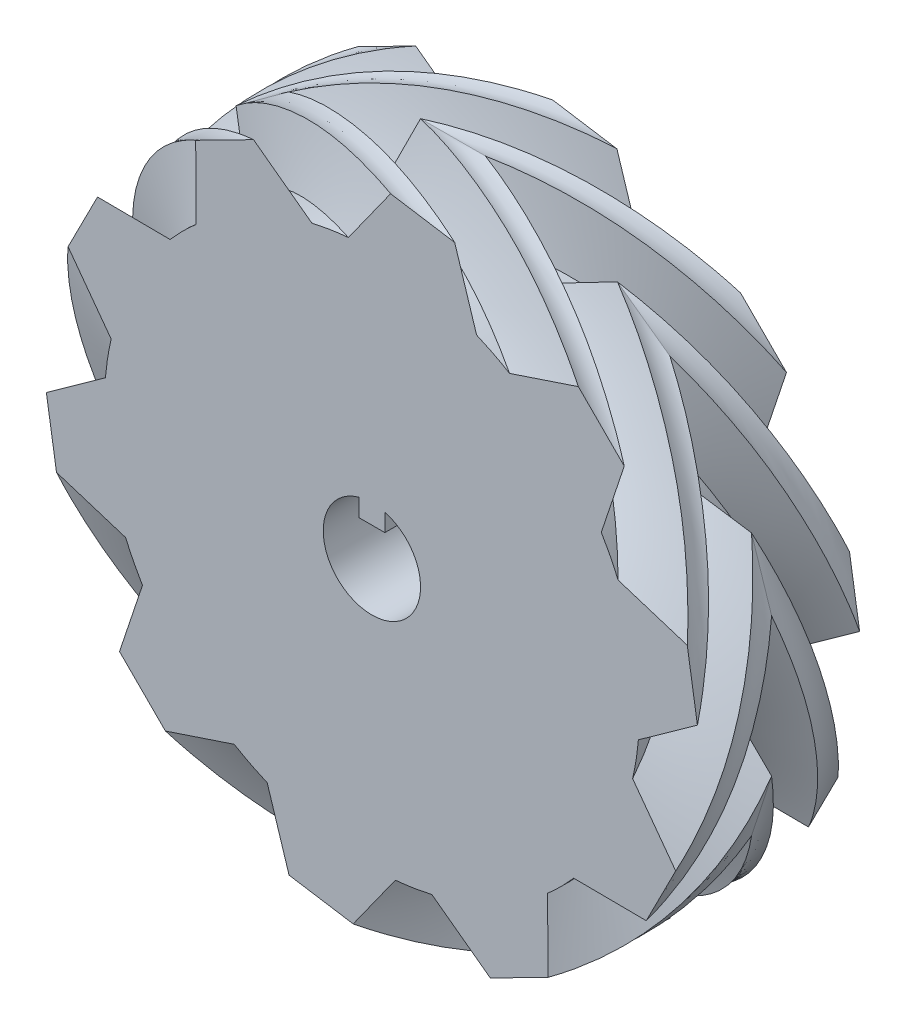
SolidWorks part; units mm, degrees
material "PETG"
ref_plane "Front Plane" through (0, 0, 0) normal (0, 0, 1) x (1, 0, 0)
ref_plane "Top Plane" through (0, 0, 0) normal (0, 1, 0) x (1, 0, 0)
ref_plane "Right Plane" through (0, 0, 0) normal (1, 0, 0) x (0, 0, -1)
sketch "Sketch1" plane through (0, 0, 0) normal (0, 0, 1) x (1, 0, 0)
  line L0 (-0.5, 5) -> (0.5, 5)
  line L1 (-0.5, 5) -> (-1, 4)
  line L2 (0.5, 5) -> (1, 4)
  line L3 (2.5344, 4.339) -> (1.5421, 3.8239)
  line L4 (2.5344, 4.339) -> (3.3434, 3.7512)
  line L5 (3.3434, 3.7512) -> (3.1602, 2.6483)
  line L6 (4.6008, 2.0206) -> (3.4952, 2.1871)
  line L7 (4.6008, 2.0206) -> (4.9098, 1.0696)
  line L8 (4.9098, 1.0696) -> (4.1132, 0.285)
  line L9 (4.9098, -1.0696) -> (4.1132, -0.285)
  line L10 (4.9098, -1.0696) -> (4.6008, -2.0206)
  line L11 (4.6008, -2.0206) -> (3.4952, -2.1871)
  line L12 (3.3434, -3.7512) -> (3.1602, -2.6483)
  line L13 (3.3434, -3.7512) -> (2.5344, -4.339)
  line L14 (2.5344, -4.339) -> (1.5421, -3.8239)
  line L15 (0.5, -5) -> (1, -4)
  line L16 (0.5, -5) -> (-0.5, -5)
  line L17 (-0.5, -5) -> (-1, -4)
  line L18 (-2.5344, -4.339) -> (-1.5421, -3.8239)
  line L19 (-2.5344, -4.339) -> (-3.3434, -3.7512)
  line L20 (-3.3434, -3.7512) -> (-3.1602, -2.6483)
  line L21 (-4.6008, -2.0206) -> (-3.4952, -2.1871)
  line L22 (-4.6008, -2.0206) -> (-4.9098, -1.0696)
  line L23 (-4.9098, -1.0696) -> (-4.1132, -0.285)
  line L24 (-4.9098, 1.0696) -> (-4.1132, 0.285)
  line L25 (-4.9098, 1.0696) -> (-4.6008, 2.0206)
  line L26 (-4.6008, 2.0206) -> (-3.4952, 2.1871)
  line L27 (-3.3434, 3.7512) -> (-3.1602, 2.6483)
  line L28 (-3.3434, 3.7512) -> (-2.5344, 4.339)
  line L29 (-2.5344, 4.339) -> (-1.5421, 3.8239)
  arc A1 (1.5421, 3.8239) -> (1, 4) centre (0, 0) ccw
  arc A2 (3.4952, 2.1871) -> (3.1602, 2.6483) centre (0, 0) ccw
  arc A3 (-1, 4) -> (-1.5421, 3.8239) centre (0, 0) ccw
  arc A4 (1, -4) -> (1.5421, -3.8239) centre (0, 0) ccw
  arc A5 (3.1602, -2.6483) -> (3.4952, -2.1871) centre (0, 0) ccw
  arc A6 (4.1132, -0.285) -> (4.1132, 0.285) centre (0, 0) ccw
  arc A7 (-3.1602, 2.6483) -> (-3.4952, 2.1871) centre (0, 0) ccw
  arc A8 (-4.1132, 0.285) -> (-4.1132, -0.285) centre (0, 0) ccw
  arc A9 (-3.4952, -2.1871) -> (-3.1602, -2.6483) centre (0, 0) ccw
  arc A10 (-1.5421, -3.8239) -> (-1, -4) centre (0, 0) ccw
  dimension "D2" = 1
  dimension "D3" = 0.5
  dimension "D4" = 5
  dimension "D5" = 2
  dimension "D1" = 1
  dimension "D6" = 10
ref_plane "Plane1" through (0, 0, 5) normal (0, 0, 1) x (1, 0, 0)
ref_plane "Plane2" through (0, 0, 10) normal (0, 0, 1) x (1, 0, 0)
sketch "Sketch3" plane through (0, 0, 0) normal (0, 0, 1) x (1, 0, 0)
  circle A0 centre (0, 0) radius 2.5
curve "Helix/Spiral1" pitch 10 height 1.25 turns 0.125
sweep "Sweep2" add profiles "Sketch1" path "Helix/Spiral1"
mirror "Mirror1" about plane through (0, 0, 0) normal (0, 0, 1) of "Sweep2"
sketch "Sketch4" plane through (0, 0, -1.25) normal (0, 0, -1) x (-1, 0, 0)
  line L0 (-0.2, 0.45) -> (0.2, 0.45)
  line L1 (0.2, 0.45) -> (0.2, 0.7228)
  line L2 (0, 55) -> (0, -55) construction
  line L3 (-0.2, 0.45) -> (-0.2, 0.7228)
  arc A0 (-0.2, 0.7228) -> (0.2, 0.7228) centre (0, 0) ccw
  point P9 (0, 0.45)
  dimension "D1" = 1.5
  dimension "D2" = 0.2
  dimension "D4" = 0.45
extrude "Cut-Extrude1" cut sketch "Sketch4" against normal through all
equation "\"rail width\"= 50"
equation "\"system width\"= 125"
equation "\"system depth\"= 250"
equation "\"internal height\"= 100"
equation "\"carriage height\"= 50"
equation "\"gear radius\"= 5"
equation "\"tooth width\"= 1"
equation "\"track width\"= 10"
equation "\"D2@Sketch1\"=\"tooth width\""
equation "\"D3@Sketch1\"=\"tooth width\"/2"
equation "\"D4@Sketch1\"=\"gear radius\""
equation "\"D5@Sketch1\"=\"tooth width\" *2"
equation "\"D1@Sketch1\"=1"
